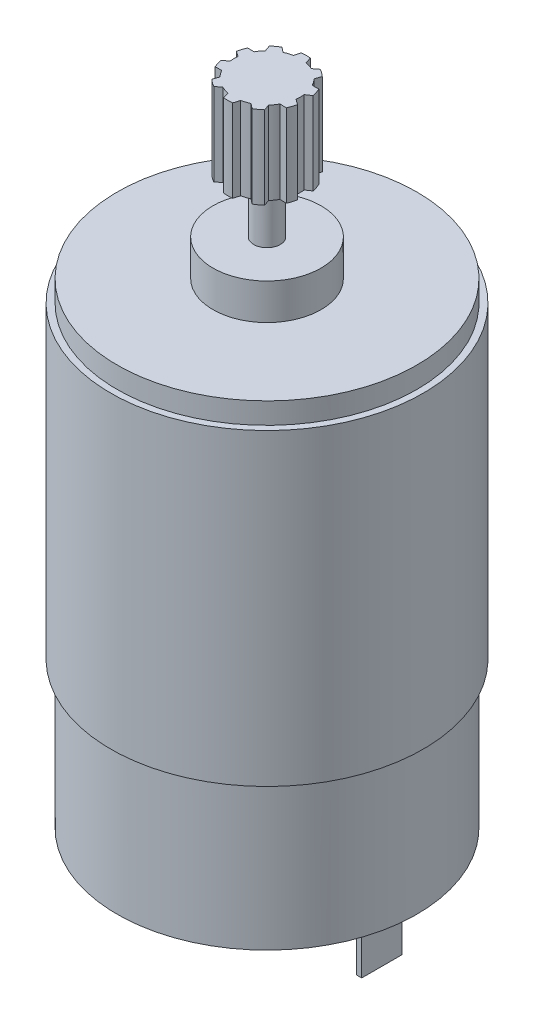
SolidWorks part; units mm, degrees
ref_plane "Front Plane" through (0, 0, 0) normal (0, 0, 1) x (1, 0, 0)
ref_plane "Top Plane" through (0, 0, 0) normal (0, 1, 0) x (1, 0, 0)
ref_plane "Right Plane" through (0, 0, 0) normal (1, 0, 0) x (0, 0, -1)
sketch "Sketch1" plane through (0, 0, 0) normal (0, 0, 1) x (1, 0, 0)
  circle A0 centre (0, 0) radius 18.6563
  dimension "D1" = 37.3126
extrude "Boss-Extrude1" [suppressed] add sketch "Sketch1" along normal mid plane 56.9214
sketch "Sketch2" [suppressed] plane through (0, 0, -28.4607) normal (0, 0, -1) x (-1, 0, 0)
  circle A0 centre (0, 0) radius 6.35
  dimension "D1" = 12.7
extrude "Boss-Extrude2" [suppressed] add sketch "Sketch2" along normal blind 4.064
sketch "Sketch3" [suppressed] plane through (0, 0, -32.5247) normal (0, 0, -1) x (-1, 0, 0)
  circle A0 centre (0, 0) radius 1.905
  dimension "D1" = 3.81
sketch "Sketch4" plane through (0, 0, 0) normal (1, 0, 0) x (0, 0, -1)
  line L0 (0, 0) -> (0, 57.023)
  line L1 (0, 57.023) -> (17.9705, 57.023)
  line L2 (17.9705, 57.023) -> (17.9705, 0)
  line L3 (17.9705, 0) -> (0, 0)
  line L4 (0, 57.023) -> (0, 61.341)
  line L5 (0, 61.341) -> (6.477, 61.341)
  line L6 (6.477, 61.341) -> (6.477, 57.023)
  line L7 (0, 61.341) -> (0, 77.851)
  line L8 (0, 77.851) -> (1.5875, 77.851)
  line L9 (1.5875, 77.851) -> (1.5875, 61.341)
  line L10 (0, -9.1792) -> (0, 103.4002) construction
  dimension "D1" = 57.023
  dimension "D2" = 17.9705
  dimension "D3" = 4.318
  dimension "D4" = 6.477
  dimension "D5" = 1.5875
  dimension "D6" = 16.51
revolve "Revolve1" add sketch "Sketch4" angle 360 about L10
sketch "Sketch5" plane through (0, 77.851, 0) normal (0, 1, 0) x (1, 0, 0)
  line L0 (-0.7579, 3.9151) -> (-0.5389, 4.6552)
  line L1 (0, 7.45) -> (0, -2.8788) construction
  line L2 (-0.5389, 4.6552) -> (0, 4.6863)
  line L3 (0.7579, 3.9151) -> (0.5389, 4.6552)
  line L4 (1.688, 3.6129) -> (2.3003, 4.0829)
  line L5 (2.9144, 2.7219) -> (3.1722, 3.4494)
  line L6 (3.4893, 1.9307) -> (4.2609, 1.951)
  line L7 (3.9577, 0.489) -> (4.5939, 0.926)
  line L8 (3.9577, -0.489) -> (4.5939, -0.926)
  line L9 (3.4893, -1.9307) -> (4.2609, -1.951)
  line L10 (2.9144, -2.7219) -> (3.1722, -3.4494)
  line L11 (1.688, -3.6129) -> (2.3003, -4.0829)
  line L12 (0.7579, -3.9151) -> (0.5389, -4.6552)
  line L13 (-0.7579, -3.9151) -> (-0.5389, -4.6552)
  line L14 (-1.688, -3.6129) -> (-2.3003, -4.0829)
  line L15 (-2.9144, -2.7219) -> (-3.1722, -3.4494)
  line L16 (-3.4893, -1.9307) -> (-4.2609, -1.951)
  line L17 (-3.9577, -0.489) -> (-4.5939, -0.926)
  line L18 (-3.9577, 0.489) -> (-4.5939, 0.926)
  line L19 (-3.4893, 1.9307) -> (-4.2609, 1.951)
  line L20 (-2.9144, 2.7219) -> (-3.1722, 3.4494)
  line L21 (-1.688, 3.6129) -> (-2.3003, 4.0829)
  circle A0 centre (0, 0) radius 4.6863
  circle A1 centre (0, 0) radius 3.9878
  point P50 (0, 0)
  dimension "D1" = 9.3726
  dimension "D2" = 7.9756
  dimension "D3" = 10
extrude "Boss-Extrude3" add sketch "Sketch5" against normal blind 9.906
sketch "Sketch6" plane through (0, 0, 0) normal (1, 0, 0) x (0, 0, -1)
  line L0 (17.9705, 54.483) -> (17.9705, 17.526)
  line L1 (17.9705, 57.023) -> (17.9705, 0) construction
  line L2 (0, 57.023) -> (17.9705, 57.023) construction
  line L3 (17.9705, 54.483) -> (18.7325, 54.483)
  line L4 (18.7325, 54.483) -> (18.7325, 17.526)
  line L5 (18.7325, 17.526) -> (17.9705, 17.526)
  dimension "D1" = 2.54
  dimension "D2" = 36.957
  dimension "D3" = 0.762
revolve "Revolve2" add sketch "Sketch6" angle 345 about L0
sketch "Sketch8" plane through (0, 0, 0) normal (0, -1, 0) x (1, 0, 0)
  line L0 (-17.9629, 0.523) -> (17.9629, 0.523) construction
  line L1 (0, 17.9705) -> (0, -17.9705) construction
  line L2 (14.2875, -1.89) -> (13.6525, 2.936) construction
  line L3 (-14.2875, -1.89) -> (-13.6525, -1.89)
  line L4 (-14.2875, -1.89) -> (-14.2875, 2.936)
  line L5 (-14.2875, 2.936) -> (-13.6525, 2.936)
  line L6 (-13.6525, -1.89) -> (-13.6525, 2.936)
  line L7 (-14.2875, -1.89) -> (-13.6525, 2.936) construction
  line L8 (-14.2875, 2.936) -> (-13.6525, -1.89) construction
  line L9 (14.2875, 2.936) -> (13.6525, -1.89) construction
  line L10 (14.2875, -1.89) -> (13.6525, -1.89)
  line L11 (13.6525, -1.89) -> (13.6525, 2.936)
  line L12 (14.2875, -1.89) -> (14.2875, 2.936)
  line L13 (14.2875, 2.936) -> (13.6525, 2.936)
  circle A0 centre (0, 0) radius 17.9705 construction
  arc A1 (4.6511, -17.3582) -> (0, -17.9705) centre (0, 0) ccw construction
  point P10 (-13.97, 0.523)
  point P15 (13.97, 0.523)
  dimension "D1" = 4.826
  dimension "D2" = 0.635
  dimension "D3" = 13.97
extrude "Boss-Extrude4" add sketch "Sketch8" along normal blind 6.985
